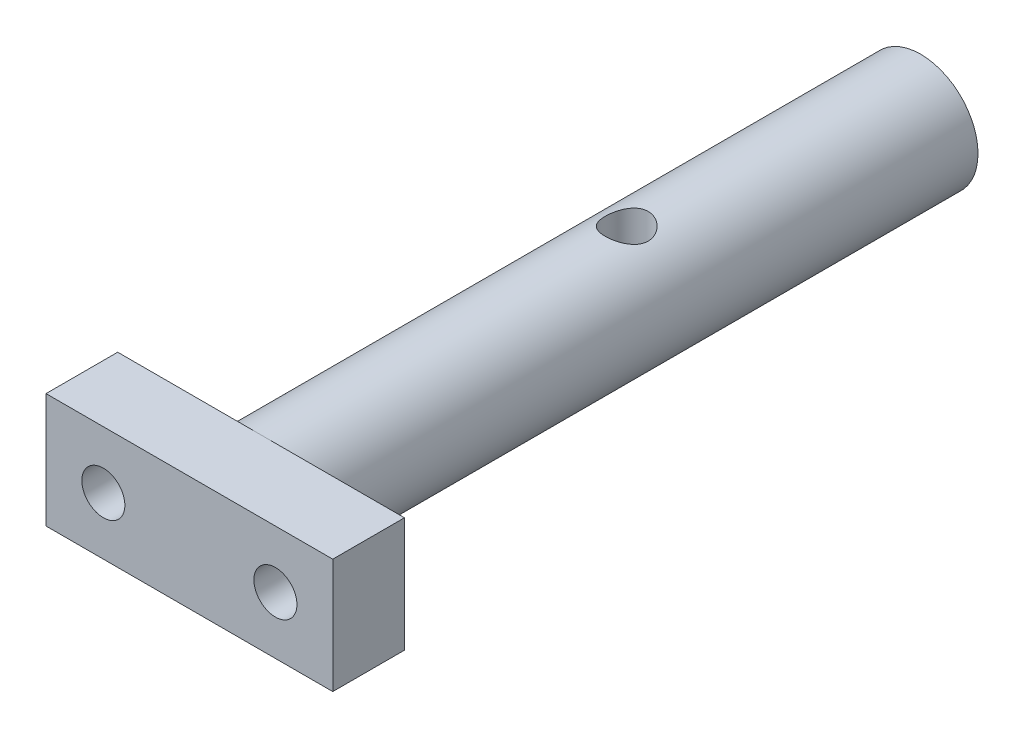
SolidWorks part; units mm, degrees
ref_plane "Alzado" through (0, 0, 0) normal (1, 0, 0) x (0, 1, 0)
ref_plane "Planta" through (0, 0, 0) normal (0, 0, 1) x (0, 1, 0)
ref_plane "Vista lateral" through (0, 0, 0) normal (0, 1, 0) x (-1, 0, 0)
sketch "Croquis1" plane through (0, 0, 0) normal (0, 0, 1) x (0, 1, 0)
  circle A0 centre (0, 0) radius 4
  dimension "D1" = 8
extrude "Saliente-Extruir1" add sketch "Croquis1" along normal blind 46
sketch "Croquis2" plane through (0, 0, 46) normal (0, 0, 1) x (1, 0, 0)
  line L1 (10, 4) -> (-10, 4)
  line L2 (10, 4) -> (10, -4)
  line L3 (10, -4) -> (-10, -4)
  line L4 (-10, 4) -> (-10, -4)
  line L5 (0, -4) -> (0, 4) construction
  line L6 (10, 0) -> (-10, 0) construction
  dimension "D2" = 8
  dimension "D3" = 20
extrude "Saliente-Extruir2" add sketch "Croquis2" along normal blind 5
sketch "Croquis3" plane through (0, 0, 51) normal (0, 0, 1) x (1, 0, 0)
  line L0 (0, 0) -> (0, -9.2151) construction
  circle A0 centre (6, 0) radius 1.5
  circle A1 centre (-6, 0) radius 1.5
  dimension "D1" = 3
  dimension "D2" = 6
extrude "Cortar-Extruir1" cut sketch "Croquis3" against normal up to next
sketch "Croquis4" plane through (0, 0, 0) normal (0, 1, 0) x (-1, 0, 0)
  line L0 (0, 0) -> (0, 20.5) construction
  circle A0 centre (0, 20.5) radius 1.5
  dimension "D2" = 3
  dimension "D1" = 20.5
extrude "Cortar-Extruir2" cut sketch "Croquis4" against normal mid plane 10
